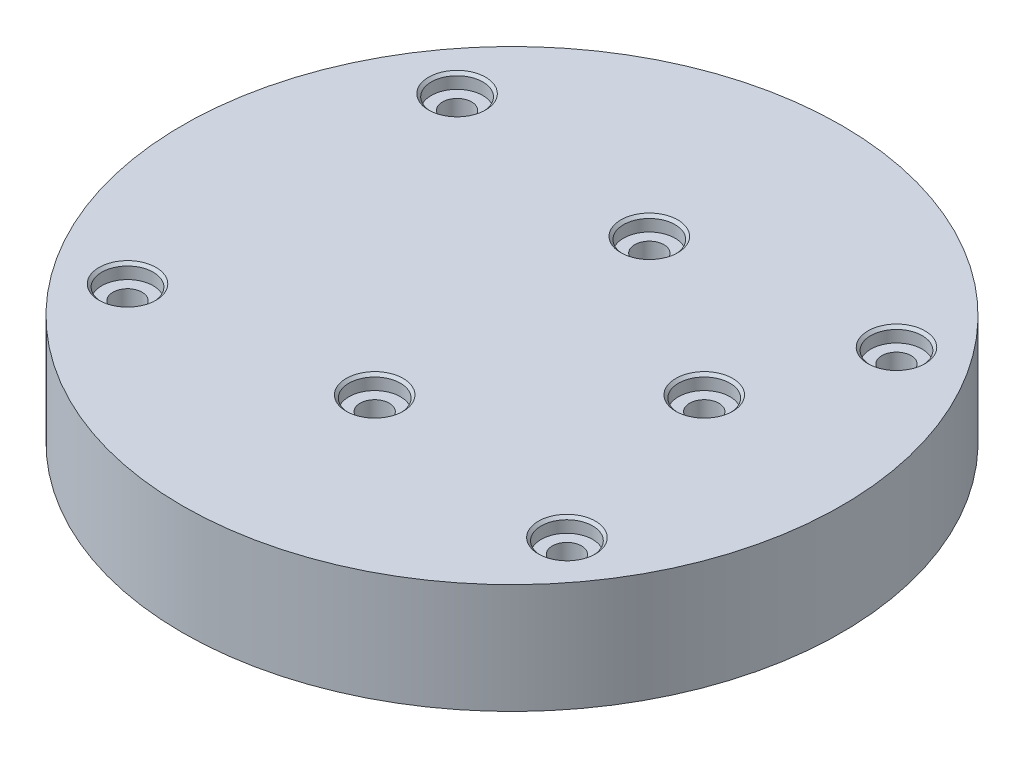
SolidWorks part; units mm, degrees
ref_plane "Front Plane" through (0, 0, 0) normal (0, 0, 1) x (1, 0, 0)
ref_plane "Top Plane" through (0, 0, 0) normal (0, 1, 0) x (1, 0, 0)
ref_plane "Right Plane" through (0, 0, 0) normal (1, 0, 0) x (0, 0, -1)
sketch "Sketch1" plane through (0, 0, 0) normal (0, 1, 0) x (1, 0, 0)
  circle A0 centre (0, 0) radius 76.2
  dimension "D1" = 152.4
extrude "Boss-Extrude1" add sketch "Sketch1" against normal blind 25.4
sketch "Sketch2" plane through (0, 0, 0) normal (0, 1, 0) x (1, 0, 0)
  line L1 (-50.8, -38.1) -> (50.8, -38.1)
  line L2 (-50.8, -38.1) -> (-50.8, 38.1)
  line L3 (-50.8, 38.1) -> (50.8, 38.1)
  line L4 (50.8, -38.1) -> (50.8, 38.1)
  line L5 (-50.8, -38.1) -> (50.8, 38.1) construction
  line L6 (-50.8, 38.1) -> (50.8, -38.1) construction
  point P0 (0, 0)
  dimension "D1" = 76.2
  dimension "D2" = 101.6
hole_wizard "CBORE for 1/4 Button Head Cap Screw1" positions "Sketch7" profile "Sketch8" counterbore size "1/4" standard "ANSI Inch" end condition up to next
sketch "Sketch7" plane through (0, 0, 0) normal (0, 1, 0) x (1, 0, 0)
  line L0 (0, 31.75) -> (0, -31.75) construction
  point P0 (0, 31.75)
  point P2 (38.1, 6.35)
  point P4 (0, -31.75)
  point P6 (50.8, -38.1)
  point P9 (50.8, 38.1)
  point P12 (-50.8, 38.1)
  point P15 (-50.8, -38.1)
  point P28 (0, 0)
  dimension "D1" = 63.5
  dimension "D2" = 38.1
  dimension "D3" = 6.35
sketch "Sketch8" plane through (0, 0, -31.75) normal (1, 0, 0) x (0, 0, 1)
  line L0 (0, 0) -> (0, 25.4)
  line L1 (0, 25.4) -> (3.3782, 25.4)
  line L3 (3.3782, 25.4) -> (3.3782, 3.3528)
  line L4 (5.9538, 3.3528) -> (3.3782, 3.3528)
  line L5 (5.9538, 3.3528) -> (5.9538, 0.635)
  line L6 (5.9538, 0.635) -> (6.5888, 0)
  line L7 (6.5888, 0) -> (0, 0)
  line L8 (-5.9538, 0.635) -> (-6.5888, 0) construction
  line L11 (0, -6.35) -> (0, 107.95) construction
  dimension "Thru Hole Dia." = 6.7564
  dimension "Thru Hole Depth" = 25.4
  dimension "C'Bore Dia." = 11.9075
  dimension "C'Bore Depth" = 3.3528
  dimension "Near C'Sink Dia." = 13.1775
  dimension "Near C'Sink Angle" = 90
